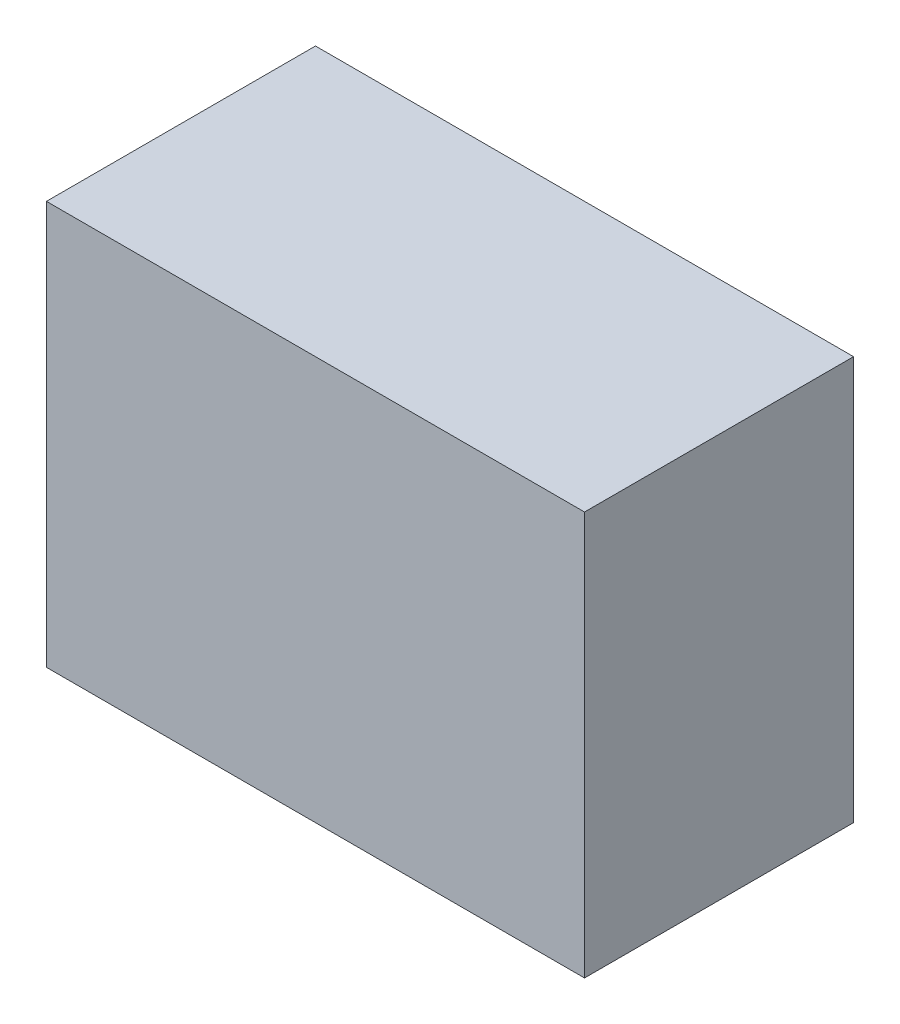
SolidWorks part; units mm, degrees
material "Gray Cast Iron"
ref_plane "Front Plane" through (0, 0, 0) normal (0, 0, 1) x (1, 0, 0)
ref_plane "Top Plane" through (0, 0, 0) normal (0, 1, 0) x (1, 0, 0)
ref_plane "Right Plane" through (0, 0, 0) normal (1, 0, 0) x (0, 0, -1)
sketch "Sketch1" plane through (0, 0, 0) normal (0, 0, 1) x (1, 0, 0)
  line L1 (0, 0) -> (400, 0)
  line L2 (0, 0) -> (0, 300)
  line L3 (0, 300) -> (400, 300)
  line L4 (400, 0) -> (400, 300)
  dimension "D1" = 400
  dimension "D2" = 300
extrude "Boss-Extrude1" add sketch "Sketch1" along normal blind 200
